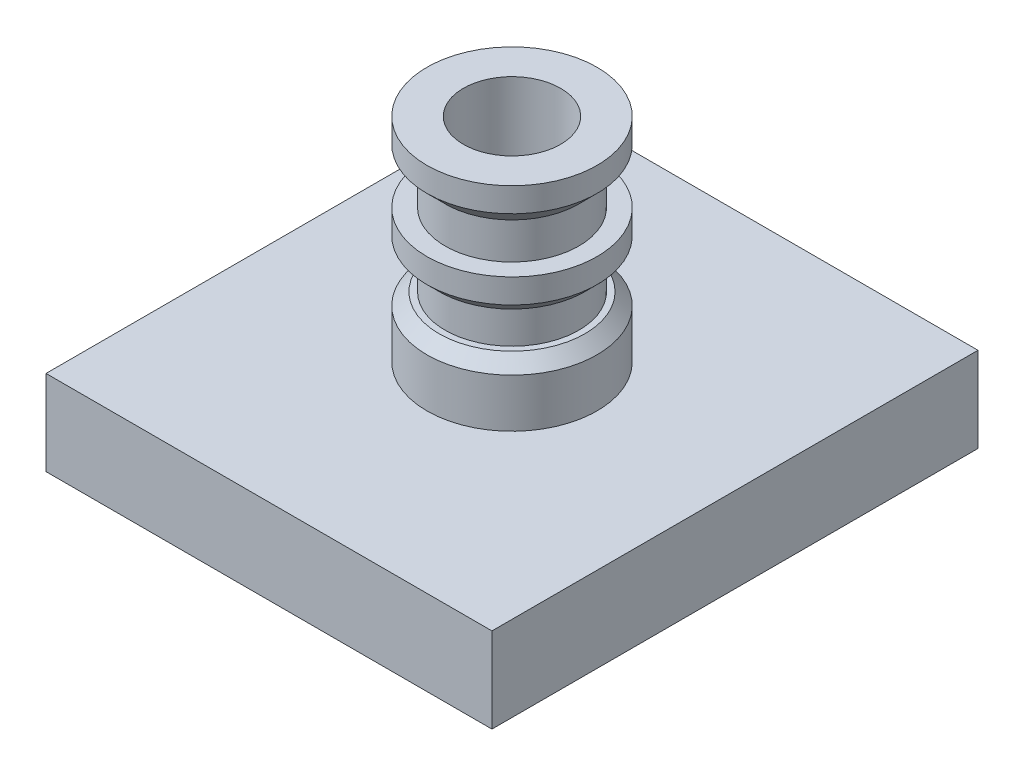
SolidWorks part; units mm, degrees
ref_plane "Alzado" through (0, 0, 0) normal (0, 0, 1) x (1, 0, 0)
ref_plane "Planta" through (0, 0, 0) normal (0, 1, 0) x (1, 0, 0)
ref_plane "Vista lateral" through (0, 0, 0) normal (1, 0, 0) x (0, 0, -1)
sketch "Croquis1" plane through (0, 0, 0) normal (0, 1, 0) x (1, 0, 0)
  line L1 (-18.35, -20) -> (18.35, -20)
  line L2 (-18.35, -20) -> (-18.35, 20)
  line L3 (-18.35, 20) -> (18.35, 20)
  line L4 (18.35, -20) -> (18.35, 20)
  line L5 (-18.35, -20) -> (18.35, 20) construction
  line L6 (-18.35, 20) -> (18.35, -20) construction
  circle A0 centre (0, 0) radius 4
  point P0 (0, 0)
  dimension "D3" = 8
  dimension "D1" = 36.7
  dimension "D2" = 40
extrude "Saliente-Extruir1" add sketch "Croquis1" along normal blind 7
sketch "Croquis2" plane through (0, 0, 0) normal (1, 0, 0) x (0, 0, -1)
  line L1 (4, 7) -> (0, 7) construction
  line L2 (0, 7) -> (0, 17.1204) construction
  line L3 (7, 7) -> (7, 12)
  line L4 (7, 12) -> (5.5, 12)
  line L5 (5.5, 12) -> (5.5, 15)
  line L6 (5.5, 15) -> (7, 15)
  line L7 (7, 15) -> (7, 18)
  line L8 (7, 18) -> (5.5, 18)
  line L9 (5.5, 18) -> (5.5, 21)
  line L10 (5.5, 21) -> (7, 22.5)
  line L11 (7, 22.5) -> (7, 24.5)
  line L12 (20, 7) -> (-20, 7) construction
  line L13 (4, 7) -> (4, 24.5)
  line L14 (4, 7) -> (-4, 7) construction
  line L15 (4, 7) -> (-4, 7) construction
  line L16 (7, 24.5) -> (4, 24.5)
  line L17 (4, 7) -> (7, 7)
  point P1 (0, 0)
  point P19 (0, 0)
  dimension "D1" = 5
  dimension "D2" = 3
  dimension "D3" = 3
  dimension "D4" = 3
  dimension "D5" = 1.5
  dimension "D6" = 7
  dimension "D7" = 5.5
  dimension "D8" = 2
revolve "Revolución1" add sketch "Croquis2" angle 360 about L2
chamfer "Chaflán1" distance 1 angle 45 2 edges at (0, 12, -7) (0, 15, -7)
sketch "Croquis3" plane through (0, 0, 0) normal (0, -1, 0) x (1, 0, 0)
  circle A0 centre (0, 0) radius 6.55
  dimension "D1" = 13.1
extrude "Cortar-Extruir1" cut sketch "Croquis3" against normal blind 2
